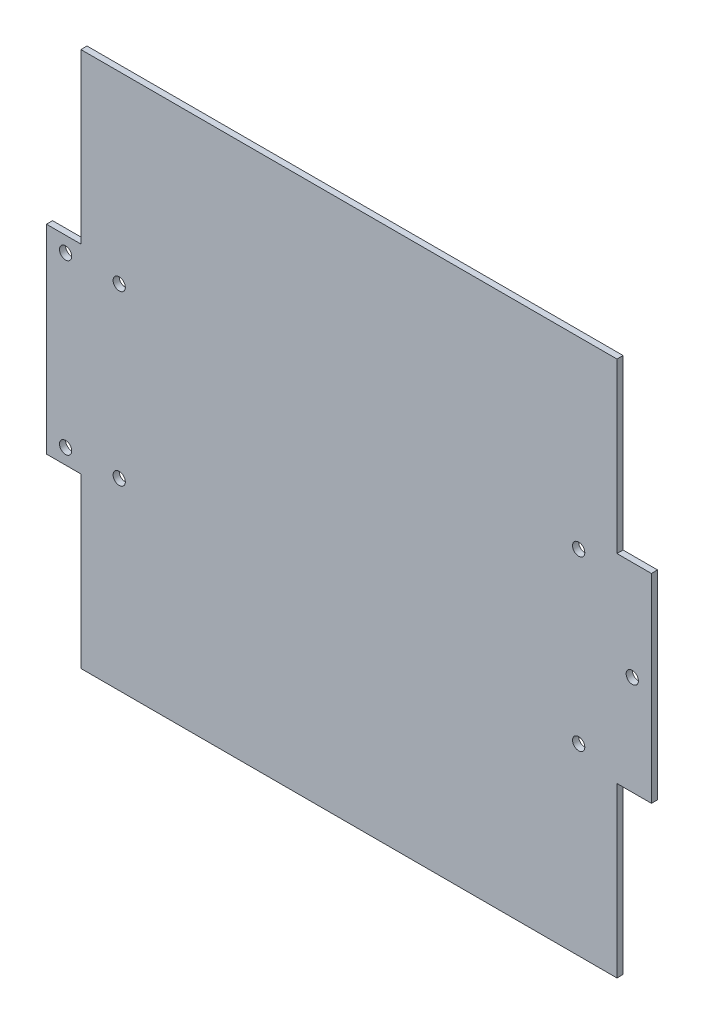
SolidWorks part; units mm, degrees
material "Custom Plastic"
ref_plane "Front Plane" through (0, 0, 0) normal (0, 0, 1) x (1, 0, 0)
ref_plane "Top Plane" through (0, 0, 0) normal (0, 1, 0) x (1, 0, 0)
ref_plane "Right Plane" through (0, 0, 0) normal (1, 0, 0) x (0, 0, -1)
sketch "Sketch1" plane through (0, 0, 0) normal (0, 0, 1) x (1, 0, 0)
  line L0 (138, 70) -> (-2, 70) construction
  line L1 (0, 0) -> (140, 0)
  line L2 (0, 0) -> (0, 44)
  line L3 (0, 140) -> (140, 140)
  line L4 (140, 0) -> (140, 44)
  line L5 (0, 96) -> (-9, 96)
  line L6 (-9, 96) -> (-9, 44)
  line L7 (-9, 44) -> (0, 44)
  line L8 (140, 44) -> (149, 44)
  line L9 (149, 44) -> (149, 96)
  line L10 (149, 96) -> (140, 96)
  line L11 (-2, 70) -> (-9, 70) construction
  line L12 (0, 96) -> (0, 140)
  line L13 (140, 96) -> (140, 140)
  dimension "D2" = 9
  dimension "D3" = 52
  dimension "D1" = 140
  dimension "D5" = 140
extrude "Boss-Extrude1" add sketch "Sketch1" along normal blind 1.6
hole_wizard "Ø3.2 (3.2) Diameter Hole1" positions "Sketch6" profile "Sketch5" hole size "Ø3.2" standard "Ansi Metric"
sketch "Sketch6" plane through (0, 0, 0) normal (0, 0, -1) x (-1, 0, 0)
  line L0 (6.0733, 70) -> (-132.5, 70) construction
  line L5 (-130, 92) -> (-130, 48) construction
  line L9 (-70, 140) -> (-70, 0) construction
  line L10 (-140, 140) -> (0, 140) construction
  line L11 (0, 0) -> (-140, 0) construction
  line L13 (-10, 92) -> (-10, 48) construction
  line L14 (-146.0733, 70) -> (-7.5, 70) construction
  point P20 (-130, 92)
  point P22 (-130, 48)
  point P48 (-10, 92)
  point P50 (-10, 48)
  dimension "D1" = 60
  dimension "D3" = 22
  dimension "D4" = 44
sketch "Sketch5" plane through (130, 92, 0) normal (1, 0, 0) x (0, 1, 0)
  line L0 (0, 0) -> (0, 4.9614)
  line L1 (0, 4.9614) -> (1.6, 4)
  line L2 (1.6, 4) -> (1.6, 0)
  line L5 (1.6, 0) -> (0, 0)
  line L10 (0, 4.9614) -> (-1.6, 4) construction
  line L11 (0, -6.35) -> (0, 107.95) construction
  dimension "Hole Dia." = 3.2
  dimension "Hole Depth" = 4
  dimension "Drill Angle" = 118
sketch "Sketch7" plane through (0, 0, 0) normal (0, 0, -1) x (-1, 0, 0)
  line L0 (-70, 140) -> (-70, 0) construction
  line L1 (-140, 140) -> (0, 140) construction
  line L2 (0, 0) -> (-140, 0) construction
  line L3 (-61.8, 132) -> (-78.2, 132) construction
  circle A0 centre (-78.2, 132) radius 1.5
  circle A1 centre (-61.8, 132) radius 1.5
  dimension "D2" = 3
  dimension "D3" = 8.2
  dimension "D1" = 8.2
  dimension "D4" = 8
extrude "Cut-Extrude1" [suppressed] cut sketch "Sketch7" against normal through all
sketch "Sketch8" plane through (0, 0, 1.6) normal (0, 0, 1) x (1, 0, 0)
  line L1 (10, 92) -> (-4, 92) construction
  line L2 (10, 92) -> (10, 48) construction
  line L3 (10, 48) -> (-4, 48) construction
  line L4 (-4, 92) -> (-4, 48) construction
  line L5 (130, 92) -> (144, 92) construction
  line L6 (130, 92) -> (130, 48) construction
  line L7 (130, 48) -> (144, 48) construction
  line L8 (144, 92) -> (144, 48) construction
  circle A0 centre (-4, 92) radius 1.6
  circle A1 centre (-4, 48) radius 1.6
  circle A2 centre (144, 70) radius 1.6
  dimension "D2" = 3.2
  dimension "D1" = 14
extrude "Cut-Extrude2" cut sketch "Sketch8" against normal through all
